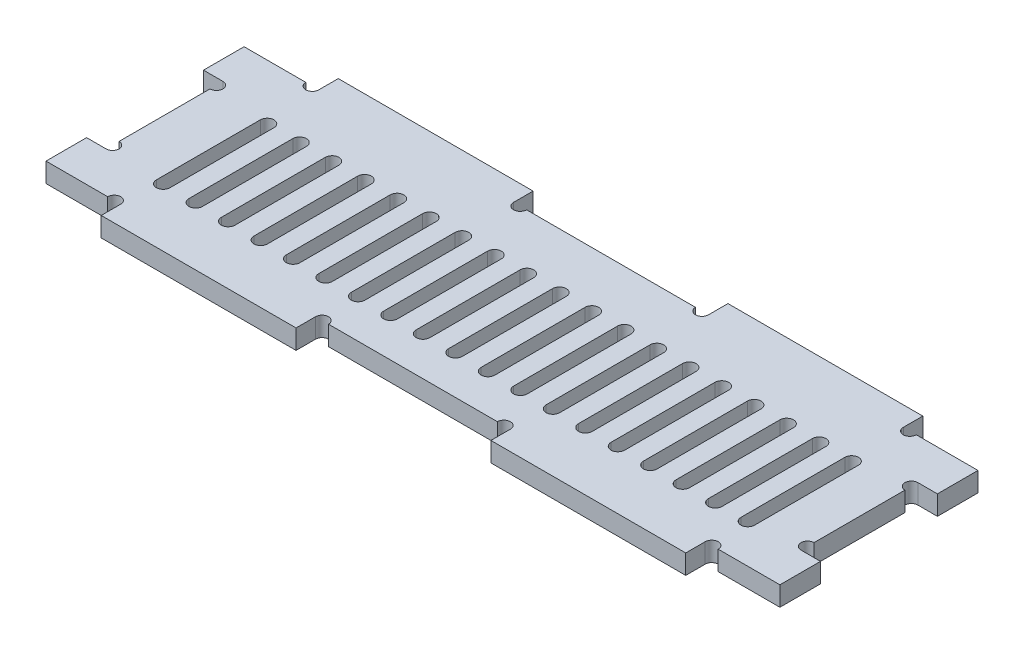
SolidWorks part; units mm, degrees
material "轻木"
ref_plane "Front" through (0, 0, 0) normal (0, 0, 1) x (1, 0, 0)
ref_plane "Top" through (0, 0, 0) normal (0, 1, 0) x (1, 0, 0)
ref_plane "Right" through (0, 0, 0) normal (1, 0, 0) x (0, 0, -1)
sketch "草图1" plane through (0, 0, 0) normal (0, 1, 0) x (1, 0, 0)
  line L0 (-47.5, 26.6) -> (-47.5, -15.2)
  line L1 (-47.5, -15.2) -> (47.5, -15.2)
  line L2 (47.5, 26.6) -> (47.5, -15.2)
  line L3 (47.5, 26.6) -> (-47.5, 26.6)
  dimension "D1" = 95
  dimension "D2" = 41.8
extrude "凸台-拉伸1" add sketch "草图1" along normal mid plane 3
sketch "草图2" plane through (0, 1.5, 0) normal (0, 1, 0) x (1, 0, 0)
  line L0 (47.5, -15.2) -> (47.5, 26.6) construction
  line L1 (-47.5, -15.2) -> (47.5, -15.2)
  line L2 (-47.5, -15.2) -> (-47.5, -7.9)
  line L3 (-47.5, -7.9) -> (47.5, -7.9)
  line L4 (47.5, -15.2) -> (47.5, -7.9)
  line L5 (-47.5, -15.2) -> (47.5, -7.9) construction
  line L6 (-47.5, -7.9) -> (47.5, -15.2) construction
  point P4 (0, -11.55)
  dimension "D1" = 7.3
extrude "切除-拉伸1" cut sketch "草图2" against normal blind 10
sketch "草图4" plane through (0, 1.5, 0) normal (0, 1, 0) x (1, 0, 0)
  line L0 (47.5, -7.9) -> (47.5, 26.6) construction
  line L1 (-47.5, 26.6) -> (47.5, 26.6)
  line L2 (-47.5, 26.6) -> (-47.5, 22.6)
  line L3 (-47.5, 22.6) -> (47.5, 22.6)
  line L4 (47.5, 26.6) -> (47.5, 22.6)
  line L5 (-47.5, 26.6) -> (47.5, 22.6) construction
  line L6 (-47.5, 22.6) -> (47.5, 26.6) construction
  point P4 (0, 24.6)
  dimension "D1" = 4
extrude "切除-拉伸3" cut sketch "草图4" against normal blind 10
sketch "草图5" plane through (0, 0, -22.6) normal (0, 0, -1) x (-1, 0, 0)
  line L0 (0, 1.5) -> (0, -7.2113) construction
  line L1 (47.5, 1.5) -> (-47.5, 1.5) construction
  line L2 (45, 1.5) -> (15, 1.5)
  line L3 (-45, -1.5) -> (-15, -1.5)
  line L4 (-45, -1.5) -> (-45, 1.5)
  line L5 (-45, 1.5) -> (-15, 1.5)
  line L6 (-15, -1.5) -> (-15, 1.5)
  line L7 (-30, 1.5) -> (-30, -1.5) construction
  line L8 (-45, 0) -> (-15, 0) construction
  line L9 (15, -1.5) -> (15, 1.5)
  line L10 (45, -1.5) -> (15, -1.5)
  line L11 (45, -1.5) -> (45, 1.5)
  point P5 (-30, 0)
  dimension "D1" = 15
  dimension "D2" = 30
extrude "凸台-拉伸2" add sketch "草图5" along normal blind 3
ref_plane "基准面1" through (0, 0, -7.35) normal (0, 0, -1) x (-1, 0, 0)
mirror "镜向1" about plane through (0, 0, -7.35) normal (0, 0, -1) of "凸台-拉伸2"
sketch "草图8" plane through (0, 1.5, 0) normal (0, 1, 0) x (1, 0, 0)
  line L0 (-52, 7.35) -> (-64.1298, 7.35) construction
  line L1 (-47.5, 22.6) -> (-56.5, 22.6)
  line L2 (-47.5, 22.6) -> (-47.5, -7.9)
  line L3 (-47.5, -7.9) -> (-56.5, -7.9)
  line L4 (-56.5, 22.6) -> (-56.5, -7.9)
  line L5 (-47.5, 22.6) -> (-56.5, -7.9) construction
  line L6 (-47.5, -7.9) -> (-56.5, 22.6) construction
  line L7 (0, 0) -> (0, 31.6146) construction
  line L8 (-53.5, -1.65) -> (-56.5, -1.65)
  line L9 (-53.5, -1.65) -> (-53.5, 16.35)
  line L10 (-53.5, 16.35) -> (-56.5, 16.35)
  line L11 (-56.5, -1.65) -> (-56.5, 16.35)
  line L12 (-55, 16.35) -> (-55, -1.65) construction
  line L13 (-53.5, 7.35) -> (-56.5, 7.35) construction
  line L14 (53.5, 7.35) -> (56.5, 7.35) construction
  line L15 (55, 16.35) -> (55, -1.65) construction
  line L16 (47.5, -7.9) -> (56.5, 22.6) construction
  line L17 (47.5, 22.6) -> (56.5, -7.9) construction
  line L18 (52, 7.35) -> (64.1298, 7.35) construction
  line L19 (56.5, -1.65) -> (56.5, 16.35)
  line L20 (53.5, 16.35) -> (56.5, 16.35)
  line L21 (53.5, -1.65) -> (53.5, 16.35)
  line L22 (53.5, -1.65) -> (56.5, -1.65)
  line L23 (56.5, 22.6) -> (56.5, -7.9)
  line L24 (47.5, -7.9) -> (56.5, -7.9)
  line L25 (47.5, 22.6) -> (47.5, -7.9)
  line L26 (47.5, 22.6) -> (56.5, 22.6)
  point P4 (-52, 7.35)
  point P9 (-55, 7.35)
  point P32 (55, 7.35)
  dimension "D1" = 9
  dimension "D2" = 3
  dimension "D3" = 18
extrude "凸台-拉伸3" add sketch "草图8" against normal up to surface (3 mm away) contours L10 L9 L8 L4 L3 L2 L1 | L26 L25 L24 L23 L22 L21 L20 up to face at (0, -1.5, -7.35)
sketch "草图7" plane through (0, 1.5, 0) normal (0, 1, 0) x (1, 0, 0)
  line L1 (-15, 22.6) -> (15, 22.6) construction
  line L2 (45, 22.6) -> (56.5, 22.6) construction
  line L3 (56.5, -7.9) -> (45, -7.9) construction
  line L4 (15, -7.9) -> (-15, -7.9) construction
  line L5 (-45, -7.9) -> (-56.5, -7.9) construction
  line L6 (-56.5, 22.6) -> (-45, 22.6) construction
  line L7 (-53.5, -1.65) -> (-53.5, 16.35) construction
  line L8 (53.5, -1.65) -> (53.5, 16.35) construction
  circle A1 centre (-14, 22.6) radius 1
  circle A2 centre (14, 22.6) radius 1
  circle A3 centre (46, 22.6) radius 1
  circle A4 centre (46, -7.9) radius 1
  circle A5 centre (14, -7.9) radius 1
  circle A6 centre (-14, -7.9) radius 1
  circle A7 centre (-46, -7.9) radius 1
  circle A8 centre (-46, 22.6) radius 1
  circle A9 centre (-53.5, 15.35) radius 1
  circle A10 centre (-53.5, -0.65) radius 1
  circle A11 centre (53.5, -0.65) radius 1
  circle A12 centre (53.5, 15.35) radius 1
  dimension "D1" = 2
extrude "切除-拉伸4" cut sketch "草图7" against normal blind 3
sketch "草图9" plane through (0, 1.5, 0) normal (0, 1, 0) x (1, 0, 0)
  line L0 (-44.45, -1.9) -> (-44.45, 14.1) construction
  line L1 (-45.5, -1.9) -> (-45.5, 14.1)
  line L2 (-43.4, -1.9) -> (-43.4, 14.1)
  line L3 (-53.5, 0.35) -> (-53.5, 14.35) construction
  line L4 (32.9413, 6.1) -> (-58.3627, 6.1) construction
  line L7 (13, -7.9) -> (-13, -7.9) construction
  arc A0 (-45.5, -1.9) -> (-43.4, -1.9) centre (-44.45, -1.9) ccw
  arc A1 (-43.4, 14.1) -> (-45.5, 14.1) centre (-44.45, 14.1) ccw
  point P3 (-44.45, 6.1)
  dimension "D1" = 2.1
  dimension "D2" = 16
  dimension "D3" = 8
  dimension "D4" = 14
extrude "切除-拉伸5" cut sketch "草图9" against normal blind 5
pattern_linear "阵列(线性)1" count 19 spacing 5 along (1, 0, 0) of "切除-拉伸5"
